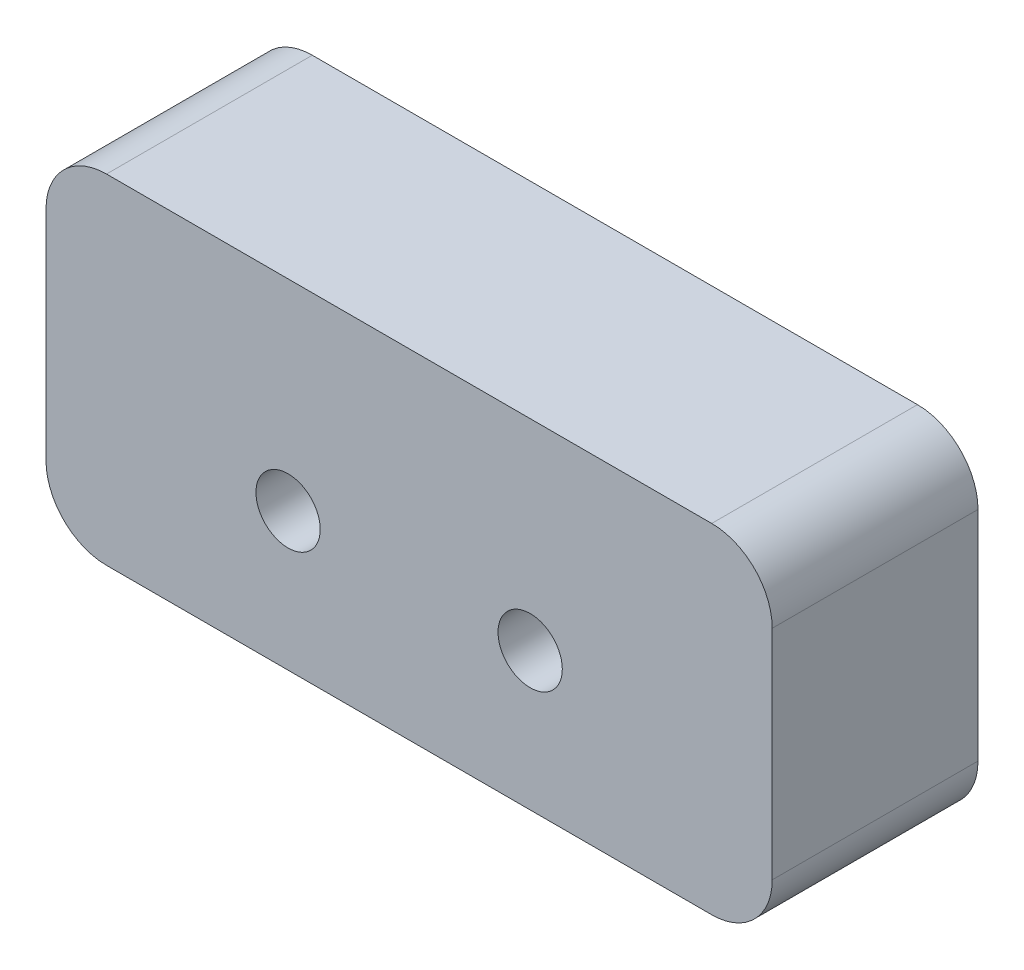
SolidWorks part; units mm, degrees
ref_plane "Front Plane" through (0, 0, 0) normal (0, 0, 1) x (1, 0, 0)
ref_plane "Top Plane" through (0, 0, 0) normal (0, 1, 0) x (1, 0, 0)
ref_plane "Right Plane" through (0, 0, 0) normal (1, 0, 0) x (0, 0, -1)
sketch "Sketch1" plane through (0, 0, 0) normal (0, 0, 1) x (1, 0, 0)
  line L0 (0, 0) -> (0, 35.56)
  line L1 (0, 35.56) -> (76.2, 35.56)
  line L2 (76.2, 35.56) -> (76.2, 0)
  line L3 (76.2, 0) -> (0, 0)
  line L5 (38.1, 35.56) -> (38.1, 0) construction
  circle A0 centre (25.4, 14.478) radius 3.3734
  circle A1 centre (50.8, 14.478) radius 3.3734
  dimension "D3" = 6.7469
  dimension "D1" = 76.2
  dimension "D2" = 35.56
  dimension "D5" = 12.7
  dimension "D6" = 12.7
  dimension "D7" = 14.478
extrude "Boss-Extrude1" add sketch "Sketch1" along normal blind 21.59
fillet "Fillet1" radius 6.35 4 edges at (76.2, 0, 10.795) (0, 0, 10.795) (76.2, 35.56, 10.795) (0, 35.56, 10.795)
sketch "Sketch2" plane through (0, 0, 0) normal (-1, 0, 0) x (0, 0, 1)
  line L0 (10.795, 6.35) -> (10.795, 29.21) construction
  line L1 (0, 6.35) -> (21.59, 6.35) construction
  line L2 (21.59, 29.21) -> (0, 29.21) construction
  line L3 (0, 35.56) -> (21.59, 35.56) construction
  point P6 (10.795, 25.4)
  dimension "D1" = 10.16
hole_wizard "1/4-20 Tapped Hole1" positions "3DSketch1" profile "Sketch3" tap size "1/4-20" standard "ANSI Inch"
sketch3d "3DSketch1"
  point P0 (0, 25.4, 10.795)
sketch "Sketch3" plane through (0, 25.4, 10.795) normal (0, 1, 0) x (0, 0, 1)
  line L0 (0, 0) -> (0, 28.2038)
  line L1 (0, 28.2038) -> (2.5527, 26.67)
  line L2 (2.5527, 26.67) -> (2.5527, 0)
  line L5 (2.5527, 0) -> (0, 0)
  line L10 (0, 28.2038) -> (-2.5527, 26.67) construction
  line L11 (0, -6.35) -> (0, 107.95) construction
  dimension "Tap Drill Dia." = 5.1054
  dimension "Tap Drill Depth" = 26.67
  dimension "Drill Angle" = 118
cosmetic thread "Hole Thread1" parameters "D1"=20.32, "D2"=6.35
equation "\"D3@Sketch1\"=\"D4@Sketch1\""
